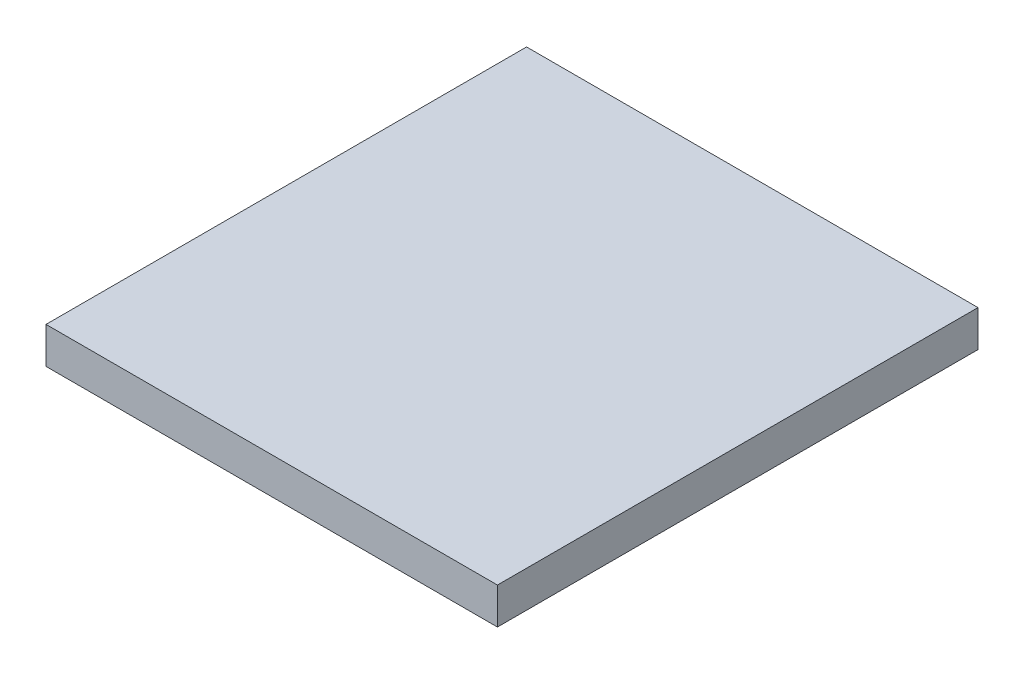
SolidWorks part; units mm, degrees
ref_plane "Front Plane" through (0, 0, 0) normal (0, 0, 1) x (1, 0, 0)
ref_plane "Top Plane" through (0, 0, 0) normal (0, 1, 0) x (1, 0, 0)
ref_plane "Right Plane" through (0, 0, 0) normal (1, 0, 0) x (0, 0, -1)
sketch "Sketch1" plane through (0, 0, 0) normal (0, 1, 0) x (1, 0, 0)
  line L0 (0, 0) -> (0, 66)
  line L1 (0, 66) -> (62, 66)
  line L2 (62, 66) -> (62, 0)
  line L3 (62, 0) -> (0, 0)
  dimension "D1" = 66
  dimension "D2" = 62
extrude "Boss-Extrude1" add sketch "Sketch1" along normal blind 5
